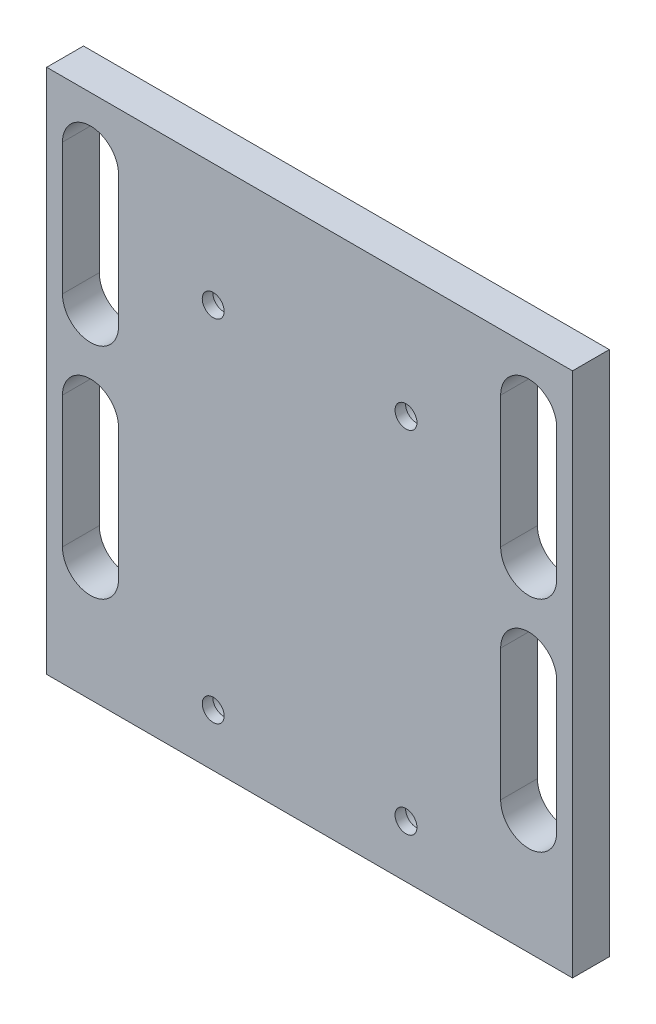
SolidWorks part; units mm, degrees
ref_plane "정면" through (0, 0, 0) normal (0, 0, 1) x (1, 0, 0)
ref_plane "윗면" through (0, 0, 0) normal (0, 1, 0) x (1, 0, 0)
ref_plane "우측면" through (0, 0, 0) normal (1, 0, 0) x (0, 0, -1)
sketch "스케치1" plane through (0, 0, 0) normal (0, 0, 1) x (1, 0, 0)
  line L0 (0, 0) -> (0, 24) construction
  line L1 (30, 34) -> (30, -26)
  line L2 (-30, -26) -> (30, -26)
  line L3 (-28.2, 0) -> (-30, 0) construction
  line L5 (0, 0) -> (-21.8, 0) construction
  line L6 (-30, -26) -> (-30, 34)
  line L7 (-30, 34) -> (30, 34)
  line L10 (-28.2, 27.5) -> (-28.2, 12.5)
  line L12 (-21.8, 27.5) -> (-21.8, 12.5)
  line L14 (-28.2, 2.5) -> (-28.2, -12.5)
  line L15 (-21.8, 2.5) -> (-21.8, -12.5)
  line L18 (21.8, 27.5) -> (21.8, 12.5)
  line L19 (28.2, 27.5) -> (28.2, 12.5)
  line L20 (21.8, 2.5) -> (21.8, -12.5)
  line L21 (28.2, 2.5) -> (28.2, -12.5)
  arc A0 (-28.2, 12.5) -> (-21.8, 12.5) centre (-25, 12.5) ccw
  circle A1 centre (-11, 20) radius 1.25
  circle A2 centre (-11, -20) radius 1.25
  arc A3 (-21.8, -12.5) -> (-28.2, -12.5) centre (-25, -12.5) cw
  arc A4 (21.8, -12.5) -> (28.2, -12.5) centre (25, -12.5) ccw
  circle A5 centre (11, -20) radius 1.25
  circle A6 centre (11, 20) radius 1.25
  arc A7 (28.2, 12.5) -> (21.8, 12.5) centre (25, 12.5) cw
  arc A8 (-21.8, 27.5) -> (-28.2, 27.5) centre (-25, 27.5) ccw
  arc A9 (-21.8, 2.5) -> (-28.2, 2.5) centre (-25, 2.5) ccw
  arc A10 (28.2, 27.5) -> (21.8, 27.5) centre (25, 27.5) ccw
  arc A11 (28.2, 2.5) -> (21.8, 2.5) centre (25, 2.5) ccw
  point P29 (0, -24)
  dimension "D1" = 2.5
  dimension "D10" = 6.4
  dimension "D2" = 11
  dimension "D3" = 14
  dimension "D4" = 6
  dimension "D5" = 20
  dimension "D6" = 30
  dimension "D8" = 25
  dimension "D9" = 12.5
extrude "보스-돌출1" add sketch "스케치1" along normal blind 4.2
sketch "스케치3" plane through (0, 0, 0) normal (0, 0, -1) x (-1, 0, 0)
  circle A0 centre (-11, 20) radius 2.5
  circle A1 centre (11, 20) radius 2.5
  circle A2 centre (-11, -20) radius 2.5
  circle A3 centre (11, -20) radius 2.5
extrude "컷-돌출2" cut sketch "스케치3" against normal blind 3
